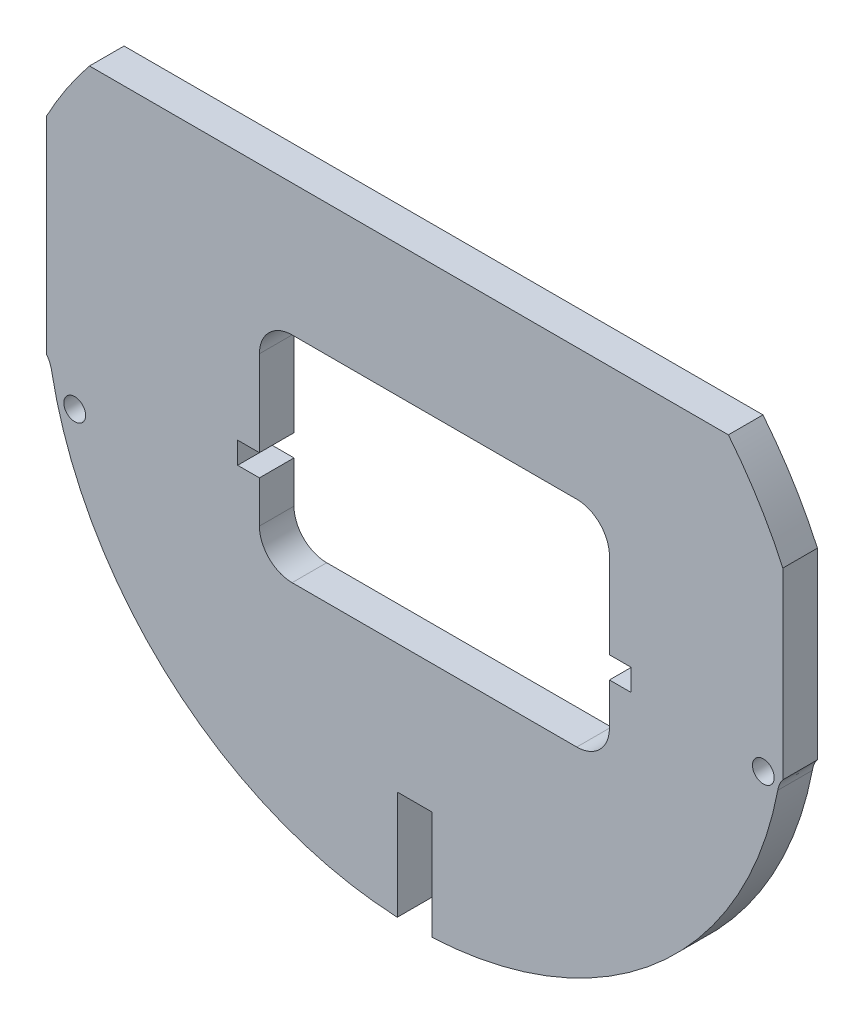
SolidWorks part; units mm, degrees
ref_plane "Front Plane" through (0, 0, 0) normal (0, 0, 1) x (1, 0, 0)
ref_plane "Top Plane" through (0, 0, 0) normal (0, 1, 0) x (1, 0, 0)
ref_plane "Right Plane" through (0, 0, 0) normal (1, 0, 0) x (0, 0, -1)
sketch "Sketch1" plane through (0, 0, 0) normal (0, 0, 1) x (1, 0, 0)
  line L3 (0, 0.1051) -> (0, 19.7996) construction
  line L10 (-33.8, 14.1039) -> (-33.8, -5.1293)
  line L12 (-29.861, 19.7996) -> (28.7983, 19.7996)
  line L14 (-33.8, 13.8554) -> (-33.8, -5.1293)
  line L15 (33.8, -5.1293) -> (33.8, 11.7035)
  line L16 (-33.8, 13.8554) -> (-33.8, -5.1293)
  line L17 (33.8, -5.1293) -> (33.8, 11.7035)
  arc A3 (-33.334, -6.1976) -> (-33.3337, -6.1989) centre (0, 0.1051) ccw
  arc A8 (-29.861, 19.7996) -> (-33.8, 13.8554) centre (-0.5314, -3.9131) ccw
  arc A11 (-33.334, -6.1976) -> (33.3337, -6.1989) centre (0, 0.1296) ccw
  arc A12 (33.8, 11.7035) -> (-33.8, 13.8554) centre (-0.5314, -3.9131) ccw
  arc A13 (-33.334, -6.1976) -> (33.3337, -6.1989) centre (0, 0.1296) ccw
  arc A14 (33.8, 11.7035) -> (28.7983, 19.7996) centre (-0.5314, -3.9131) ccw
  spline S6 degree 3 poles (-2871.0658, -2823.4806) (2731.1475, 2929.8379) (-2727.7416, -3009.8674) (2594.7754, 3008.9319) knots -33.831724 -33.831724 -33.831724 -33.831724 36.920688 36.920688 36.920688 36.920688 only from (-33.8, -5.1293) to (-33.334, -6.1976)
  spline S7 degree 3 poles (-3766.362, 1242.7106) (156.1418, -78.1057) (27.9378, -19.0879) (38.2051, 5.7649) (145.4668, -11.9373) (1026.3545, -3878.103) knots -36.6758 -36.6758 -36.6758 -36.6758 0.5 0.5 32.001604 32.001604 32.001604 32.001604 only from (33.3337, -6.1989) to (33.8, -5.1293)
  spline S8 degree 3 poles (-33.8, -5.1293) (-33.542, -5.431) (-33.4073, -5.8094) (-33.334, -6.1976) knots 0 0 0 0 1 1 1 1
  spline S9 degree 3 poles (33.3337, -6.1989) (33.3703, -6.005) (33.4208, -5.8158) (33.5703, -5.4539) (33.6709, -5.2803) (33.8, -5.1293) knots 0 0 0 0 0.5 0.5 1 1 1 1
  spline S13 degree 3 poles (-2980.5666, -2708.2928) (-118.9114, 25.5573) (-37.2715, 3.8481) (-28.8046, -17.4149) (-135.1556, -20.8541) (3679.8133, -1492.2014) knots -26.020725 -26.020725 -26.020725 -26.020725 0.5 0.5 33.277666 33.277666 33.277666 33.277666 only from (-33.8, -5.1293) to (-33.3337, -6.1989)
  spline S14 degree 3 poles (-33.334, -6.1976) (-33.3339, -6.198) (-33.3338, -6.1985) (-33.3337, -6.1989) knots 0.998749 0.998749 0.998749 0.998749 1 1 1 1
  point P4 (0, 19.7996)
  dimension "D1" = 1
  dimension "D2" = 1
extrude "Boss-Extrude1" add sketch "Sketch1" along normal mid plane 3.175
sketch "Sketch2" plane through (0, 0, 1.5875) normal (0, 0, 1) x (1, 0, 0)
  circle A1 centre (-31.2161, -8.1644) radius 1
  circle A2 centre (-31.2161, -8.1644) radius 1
  circle A3 centre (32.0093, -5.359) radius 1
  circle A4 centre (32.0093, -5.359) radius 1
  dimension "D1" = 0
  dimension "D2" = 0
extrude "Cut-Extrude1" cut sketch "Sketch2" against normal blind 3.175
sketch "Sketch3" plane through (0, 0, 1.5875) normal (0, 0, 1) x (1, 0, 0)
  line L0 (-1.6006, -23.7996) -> (-1.6006, -34.7702) construction
  line L1 (-1.6006, -34.7702) -> (1.5744, -34.7702) construction
  line L2 (1.5744, -34.7702) -> (1.5744, -23.7996) construction
  line L3 (-1.6006, -23.7996) -> (1.5744, -23.7996) construction
  line L4 (-1.6006, -23.7996) -> (-1.6006, -34.7702)
  line L5 (-1.6006, -34.7702) -> (1.5744, -34.7702)
  line L6 (1.5744, -34.7702) -> (1.5744, -23.7996)
  line L7 (-1.6006, -23.7996) -> (1.5744, -23.7996)
extrude "Cut-Extrude2" cut sketch "Sketch3" against normal through all
sketch "Sketch4" plane through (0, 0, 1.5875) normal (0, 0, 1) x (1, 0, 0)
  line L6 (19.8786, -3.1502) -> (19.8786, -5.1502) construction
  line L36 (19.8786, -5.1502) -> (17.8786, -5.1502) construction
  line L38 (17.8786, -5.1502) -> (17.8786, -3.1502) construction
  line L104 (17.8786, -3.1502) -> (19.8786, -3.1502) construction
  line L105 (-11.2577, -11.9843) -> (14.8786, -11.9843)
  line L106 (17.8786, -8.9843) -> (17.8786, 4.7172)
  line L107 (14.8786, 7.7172) -> (-11.2577, 7.7172)
  line L108 (-14.2577, 4.7172) -> (-14.2577, -8.9843)
  line L109 (-11.2577, -11.9843) -> (14.8786, -11.9843)
  line L110 (17.8786, -8.9843) -> (17.8786, 4.7172)
  line L111 (14.8786, 7.7172) -> (-11.2577, 7.7172)
  line L112 (-14.2577, 4.7172) -> (-14.2577, -8.9843)
  line L116 (-14.2577, -3.1502) -> (-16.2577, -3.1502) construction
  line L117 (-14.2577, -5.1502) -> (-14.2577, -3.1502) construction
  line L118 (-16.2577, -5.1502) -> (-14.2577, -5.1502) construction
  line L123 (-16.2577, -3.1502) -> (-16.2577, -5.1502) construction
  line L124 (19.8786, -3.1502) -> (19.8786, -5.1502)
  line L125 (19.8786, -5.1502) -> (17.8786, -5.1502)
  line L126 (17.8786, -5.1502) -> (17.8786, -3.1502)
  line L127 (17.8786, -3.1502) -> (19.8786, -3.1502)
  line L131 (-14.2577, -3.1502) -> (-16.2577, -3.1502)
  line L132 (-14.2577, -5.1502) -> (-14.2577, -3.1502)
  line L133 (-16.2577, -5.1502) -> (-14.2577, -5.1502)
  line L138 (-16.2577, -3.1502) -> (-16.2577, -5.1502)
  arc A108 (14.8786, -11.9843) -> (17.8786, -8.9843) centre (14.8786, -8.9843) ccw
  arc A109 (17.8786, 4.7172) -> (14.8786, 7.7172) centre (14.8786, 4.7172) ccw
  arc A110 (-11.2577, 7.7172) -> (-14.2577, 4.7172) centre (-11.2577, 4.7172) ccw
  arc A111 (-14.2577, -8.9843) -> (-11.2577, -11.9843) centre (-11.2577, -8.9843) ccw
  arc A112 (14.8786, -11.9843) -> (17.8786, -8.9843) centre (14.8786, -8.9843) ccw
  arc A113 (17.8786, 4.7172) -> (14.8786, 7.7172) centre (14.8786, 4.7172) ccw
  arc A114 (-11.2577, 7.7172) -> (-14.2577, 4.7172) centre (-11.2577, 4.7172) ccw
  arc A115 (-14.2577, -8.9843) -> (-11.2577, -11.9843) centre (-11.2577, -8.9843) ccw
  dimension "D1" = 0
extrude "Cut-Extrude3" cut sketch "Sketch4" against normal through all contours L112 A115 L109 A112 L110 A113 L111 A114 | L131 L138 L133 L112 | L127 L110 L125 L124
